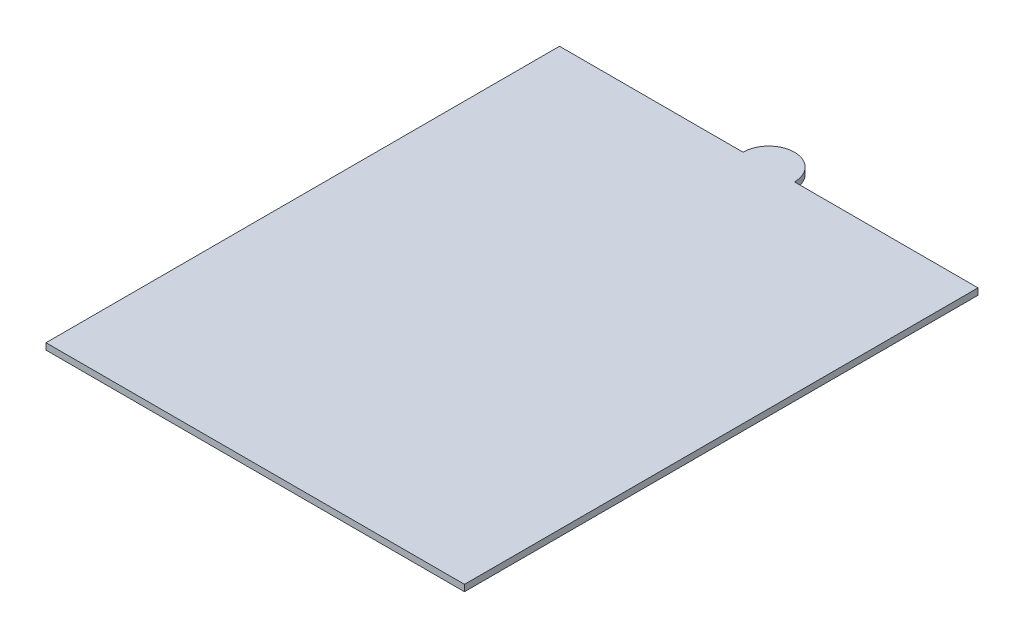
SolidWorks part; units mm, degrees
material "Acrylic (Medium-high impact)"
ref_plane "Front" through (0, 0, 0) normal (0, 0, 1) x (1, 0, 0)
ref_plane "Top" through (0, 0, 0) normal (0, 1, 0) x (1, 0, 0)
ref_plane "Right" through (0, 0, 0) normal (1, 0, 0) x (0, 0, -1)
sketch "Sketch1" plane through (0, 0, 0) normal (0, 1, 0) x (1, 0, 0)
  line L0 (12.7, 126.619) -> (103.1875, 126.619)
  line L1 (-103.1875, -126.619) -> (103.1875, -126.619)
  line L2 (-103.1875, -126.619) -> (-103.1875, 126.619)
  line L3 (-103.1875, 126.619) -> (-12.7, 126.619)
  line L4 (103.1875, -126.619) -> (103.1875, 126.619)
  line L5 (-103.1875, -126.619) -> (103.1875, 126.619) construction
  line L6 (-103.1875, 126.619) -> (103.1875, -126.619) construction
  arc A0 (12.7, 126.619) -> (-12.7, 126.619) centre (0, 126.619) ccw
  point P0 (0, 0)
  dimension "D3" = 25.4
  dimension "D1" = 206.375
  dimension "D2" = 253.238
extrude "Boss-Extrude1" add sketch "Sketch1" along normal blind 3.175
